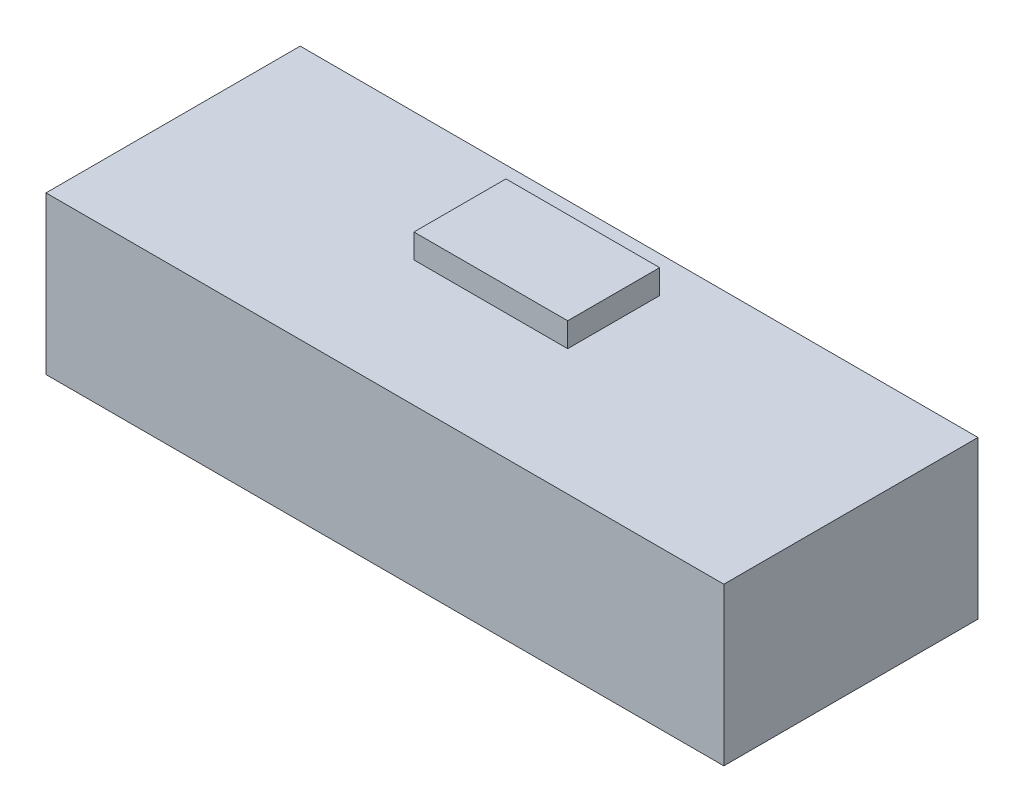
SolidWorks part; units mm, degrees
ref_plane "Front Plane" through (0, 0, 0) normal (0, 0, 1) x (1, 0, 0)
ref_plane "Top Plane" through (0, 0, 0) normal (0, 1, 0) x (1, 0, 0)
ref_plane "Right Plane" through (0, 0, 0) normal (1, 0, 0) x (0, 0, -1)
sketch "SK_P01_F2inlineholder5A" plane through (0, 0, 0) normal (0, 1, 0) x (1, 0, 0)
  line L0 (-28, -10.5) -> (28, -10.5)
  line L1 (28, -10.5) -> (28, 10.5)
  line L2 (28, 10.5) -> (-28, 10.5)
  line L3 (-28, 10.5) -> (-28, -10.5)
extrude "P01_F2inlineholder5A" add sketch "SK_P01_F2inlineholder5A" along normal blind 13
sketch "SK_P02_D1idealdiodePololu5382" plane through (0, 0, 0) normal (0, 1, 0) x (1, 0, 0)
  line L0 (-8, -0.1) -> (4.7, -0.1)
  line L1 (4.7, -0.1) -> (4.7, 7.5)
  line L2 (4.7, 7.5) -> (-8, 7.5)
  line L3 (-8, 7.5) -> (-8, -0.1)
extrude "P02_D1idealdiodePololu5382" add sketch "SK_P02_D1idealdiodePololu5382" along normal blind 2 from offset 13
